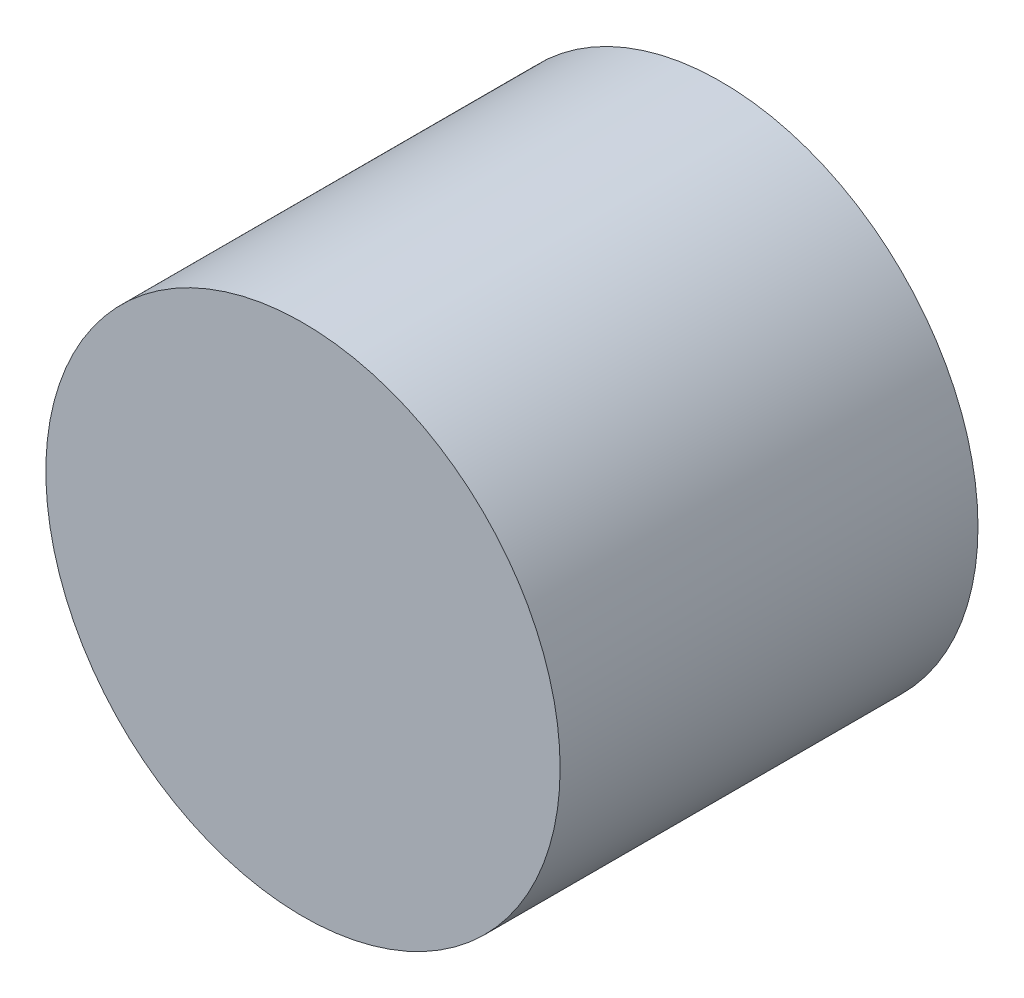
SolidWorks part; units mm, degrees
ref_plane "Front Plane" through (0, 0, 0) normal (0, 0, 1) x (1, 0, 0)
ref_plane "Top Plane" through (0, 0, 0) normal (0, 1, 0) x (1, 0, 0)
ref_plane "Right Plane" through (0, 0, 0) normal (1, 0, 0) x (0, 0, -1)
sketch "Sketch1" plane through (0, 0, 0) normal (0, 0, 1) x (1, 0, 0)
  circle A0 centre (0, 0) radius 10.16
  dimension "D1" = 20.32
extrude "Boss-Extrude1" add sketch "Sketch1" along normal blind 16.51
